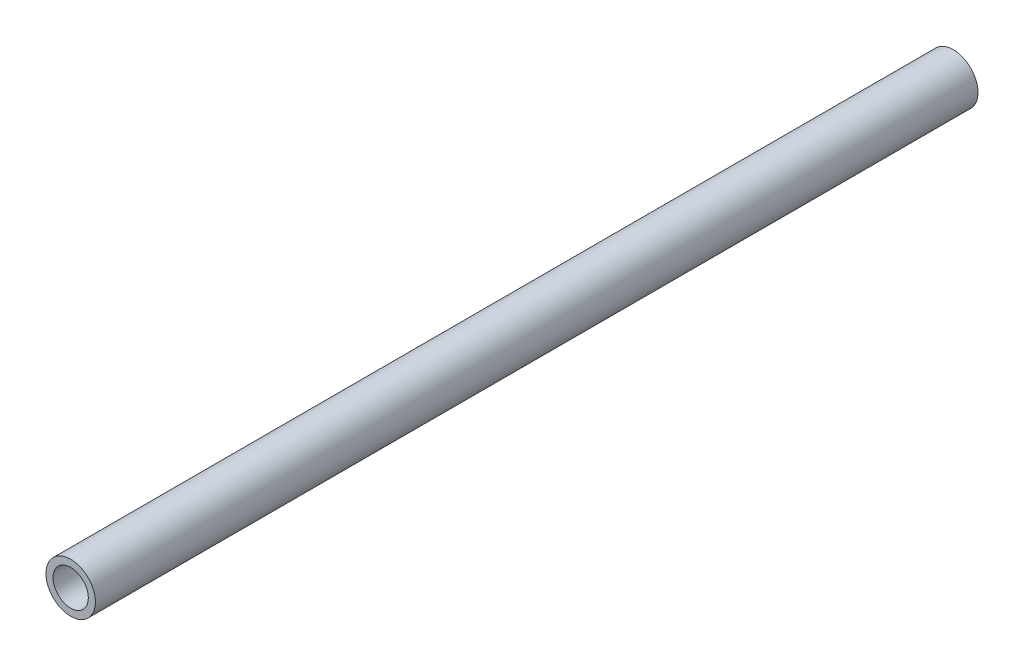
SolidWorks part; units mm, degrees
material "EM-CF"
ref_plane "Płaszczyzna przednia" through (0, 0, 0) normal (0, 0, 1) x (1, 0, 0)
ref_plane "Płaszczyzna górna" through (0, 0, 0) normal (0, 1, 0) x (1, 0, 0)
ref_plane "Płaszczyzna prawa" through (0, 0, 0) normal (1, 0, 0) x (0, 0, -1)
sketch "Szkic1" plane through (0, 0, 0) normal (0, 0, 1) x (1, 0, 0)
  circle A0 centre (0, 0) radius 5
  circle A1 centre (0, 0) radius 7
  dimension "D1" = 2
  dimension "D2" = 14
extrude "Dodanie-wyciągnięcie1" add sketch "Szkic1" along normal blind 250
